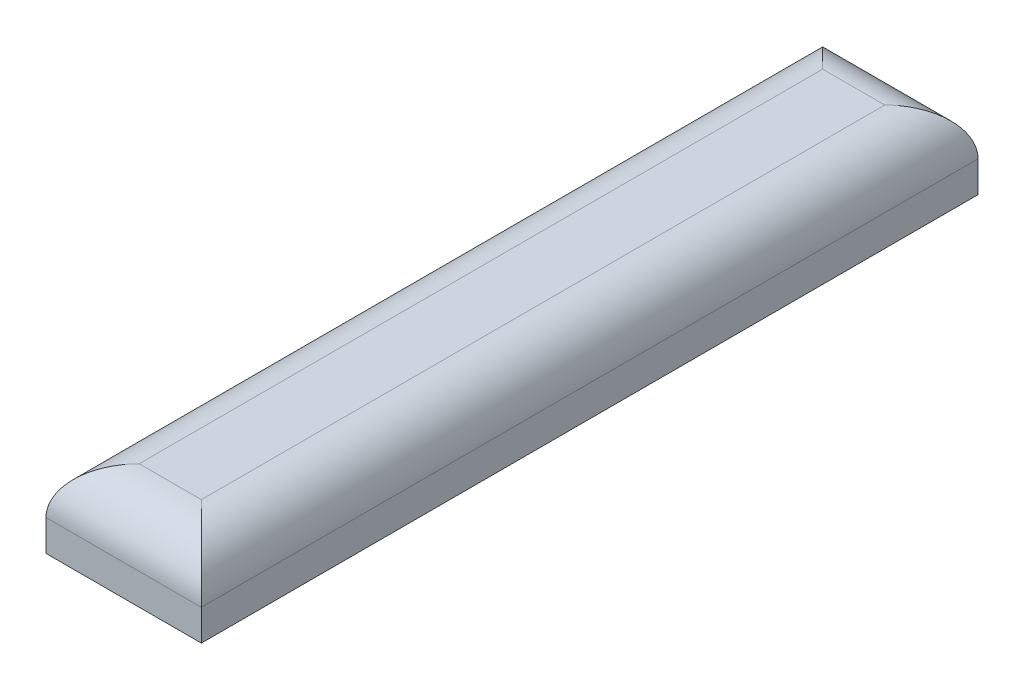
SolidWorks part; units mm, degrees
material "Rubber"
ref_plane "Front Plane" through (0, 0, 0) normal (0, 0, 1) x (1, 0, 0)
ref_plane "Top Plane" through (0, 0, 0) normal (0, 1, 0) x (1, 0, 0)
ref_plane "Right Plane" through (0, 0, 0) normal (1, 0, 0) x (0, 0, -1)
sketch "Sketch1" plane through (0, 0, 0) normal (0, 1, 0) x (1, 0, 0)
  line L1 (-12.7, 63.5) -> (12.7, 63.5)
  line L2 (-12.7, 63.5) -> (-12.7, -63.5)
  line L3 (-12.7, -63.5) -> (12.7, -63.5)
  line L4 (12.7, 63.5) -> (12.7, -63.5)
  line L5 (-12.7, 63.5) -> (12.7, -63.5) construction
  line L6 (-12.7, -63.5) -> (12.7, 63.5) construction
  point P0 (0, 0)
  dimension "D1" = 25.4
  dimension "D2" = 127
extrude "Boss-Extrude1" add sketch "Sketch1" along normal blind 12.7
fillet "Fillet1" radius 7.62 4 edges at (0, 12.7, 63.5) (-12.7, 12.7, 0) (0, 12.7, -63.5) (12.7, 12.7, 0)
